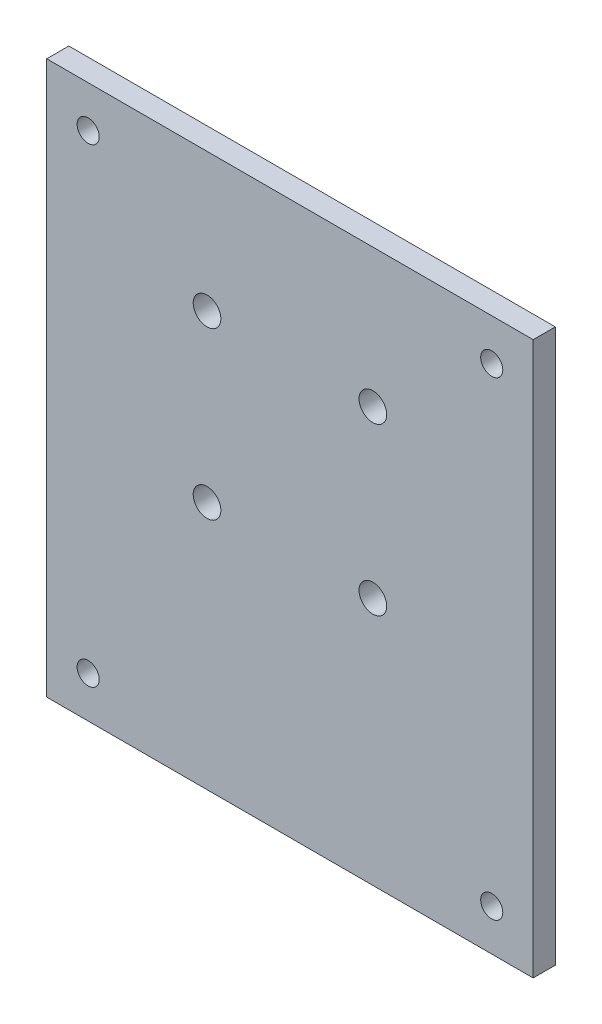
SolidWorks part; units mm, degrees
material "A-玻璃纤维"
ref_plane "前视基准面" through (0, 0, 0) normal (0, 0, 1) x (1, 0, 0)
ref_plane "上视基准面" through (0, 0, 0) normal (0, 1, 0) x (1, 0, 0)
ref_plane "右视基准面" through (0, 0, 0) normal (1, 0, 0) x (0, 0, -1)
sketch "草图1" plane through (0, 0, 0) normal (0, 0, 1) x (1, 0, 0)
  line L1 (-44, 50) -> (44, 50)
  line L2 (-44, 50) -> (-44, -50)
  line L3 (-44, -50) -> (44, -50)
  line L4 (44, 50) -> (44, -50)
  line L5 (-44, 50) -> (44, -50) construction
  line L6 (-44, -50) -> (44, 50) construction
  point P0 (0, 0)
  dimension "D1" = 88
  dimension "D2" = 100
extrude "凸台-拉伸1" add sketch "草图1" along normal blind 4
sketch "草图2" plane through (0, 0, 4) normal (0, 0, 1) x (1, 0, 0)
  line L0 (44, -50) -> (44, 50) construction
  line L1 (-36.5, 42.5) -> (36.5, 42.5) construction
  line L2 (-36.5, 42.5) -> (-36.5, -42.5) construction
  line L3 (-36.5, -42.5) -> (36.5, -42.5) construction
  line L4 (36.5, 42.5) -> (36.5, -42.5) construction
  line L5 (-36.5, 42.5) -> (36.5, -42.5) construction
  line L6 (-36.5, -42.5) -> (36.5, 42.5) construction
  line L7 (-44, -50) -> (44, -50) construction
  circle A0 centre (-36.5, 42.5) radius 2
  circle A1 centre (36.5, 42.5) radius 2
  circle A2 centre (36.5, -42.5) radius 2
  circle A3 centre (-36.5, -42.5) radius 2
  point P0 (0, 0)
  dimension "D1" = 4
  dimension "D2" = 7.5
  dimension "D3" = 7.5
extrude "切除-拉伸1" cut sketch "草图2" against normal through all
sketch "草图3" plane through (0, 0, 4) normal (0, 0, 1) x (1, 0, 0)
  line L0 (0, 50) -> (0, -50) construction
  line L1 (44, 50) -> (-44, 50) construction
  line L2 (-44, -50) -> (44, -50) construction
  line L4 (-15, 25) -> (15, 25) construction
  line L5 (-15, 25) -> (-15, -5) construction
  line L6 (-15, -5) -> (15, -5) construction
  line L7 (15, 25) -> (15, -5) construction
  line L8 (-15, 25) -> (15, -5) construction
  line L9 (-15, -5) -> (15, 25) construction
  circle A0 centre (-15, 25) radius 2.5
  circle A1 centre (15, 25) radius 2.5
  circle A2 centre (15, -5) radius 2.5
  circle A3 centre (-15, -5) radius 2.5
  point P6 (0, 10)
  dimension "D4" = 5
  dimension "D1" = 30
  dimension "D2" = 30
  dimension "D3" = 60
extrude "切除-拉伸2" cut sketch "草图3" against normal through all
